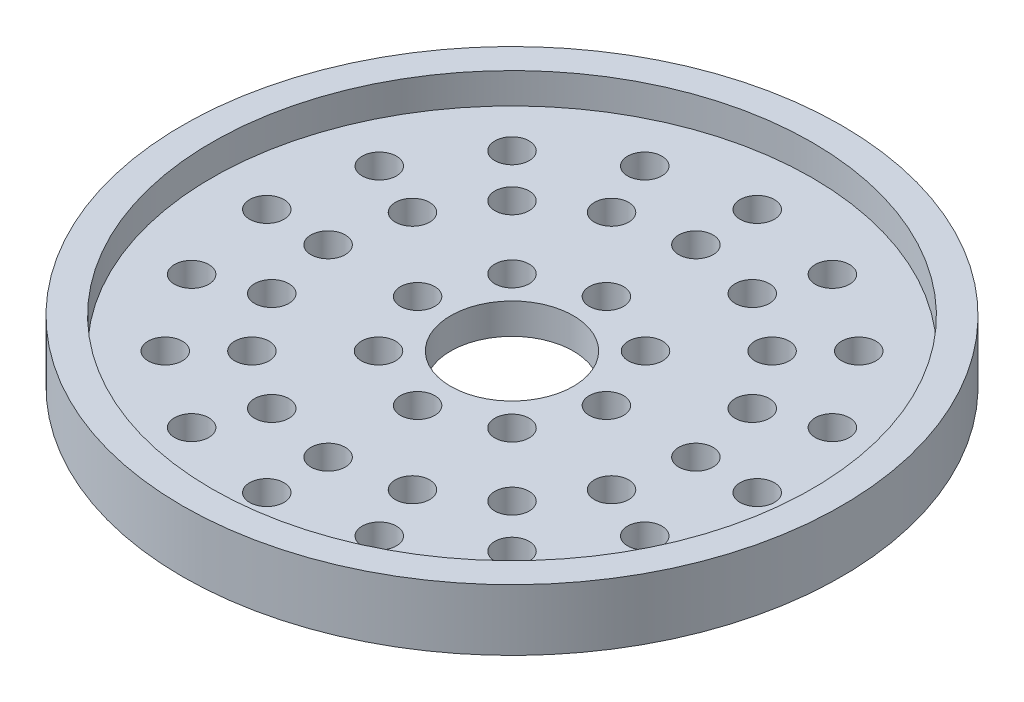
SolidWorks part; units mm, degrees
material "6061-T6 (SS)"
ref_plane "Front Plane" through (0, 0, 0) normal (0, 0, 1) x (1, 0, 0)
ref_plane "Top Plane" through (0, 0, 0) normal (0, 1, 0) x (1, 0, 0)
ref_plane "Right Plane" through (0, 0, 0) normal (1, 0, 0) x (0, 0, -1)
sketch "Sketch1" plane through (0, 0, 0) normal (0, 1, 0) x (1, 0, 0)
  circle A0 centre (0, 0) radius 34.1376
  dimension "D1" = 68.2752
extrude "Boss-Extrude1" add sketch "Sketch1" along normal blind 6.35
sketch "Sketch2" plane through (0, 6.35, 0) normal (0, 1, 0) x (1, 0, 0)
  circle A0 centre (0, 0) radius 31.0896
  circle A1 centre (0, 0) radius 34.1376 construction
  dimension "D1" = 3.048
extrude "Cut-Extrude3" cut sketch "Sketch2" against normal blind 3.175
sketch "Sketch3" plane through (0, 3.175, 0) normal (0, 1, 0) x (1, 0, 0)
  line L0 (0, 0) -> (0, 25.4) construction
  line L1 (0, 0) -> (0, -25.4) construction
  line L2 (0, 0) -> (25.4, 0) construction
  line L3 (0, 0) -> (-25.4, 0) construction
  line L4 (0, 0) -> (17.9605, 17.9605) construction
  line L5 (0, 0) -> (-17.9605, 17.9605) construction
  line L6 (0, 0) -> (-17.9605, -17.9605) construction
  line L7 (0, 0) -> (17.9605, -17.9605) construction
  circle A0 centre (0, 0) radius 6.35
  circle A1 centre (25.4, 0) radius 1.778
  circle A2 centre (17.9605, 17.9605) radius 1.778
  circle A3 centre (0, 25.4) radius 1.778
  circle A4 centre (-17.9605, 17.9605) radius 1.778
  circle A5 centre (-25.4, 0) radius 1.778
  circle A6 centre (-17.9605, -17.9605) radius 1.778
  circle A7 centre (0, -25.4) radius 1.778
  circle A8 centre (17.9605, -17.9605) radius 1.778
  dimension "D1" = 12.7
  dimension "D2" = 3.556
  dimension "D3" = 25.4
  dimension "D4" = 35.921
  dimension "D5" = 35.921
extrude "Cut-Extrude4" cut sketch "Sketch3" against normal blind 3.175 contours A0
sketch "Sketch7" plane through (0, 3.175, 0) normal (0, 1, 0) x (1, 0, 0)
  line L0 (0, 0) -> (0, 25.4) construction
  line L1 (0, 0) -> (0, 19.05) construction
  line L2 (0, 0) -> (0, 9.779) construction
  line L3 (-3.5469, 0) -> (3.6351, 0) construction
  line L4 (0, 0) -> (25.4, 0) construction
  line L5 (0, 0) -> (19.05, 0) construction
  line L6 (0, 0) -> (9.779, 0) construction
  line L7 (0, 0) -> (17.9605, 17.9605) construction
  line L8 (0, 0) -> (13.4704, 13.4704) construction
  line L9 (0, 0) -> (6.9148, 6.9148) construction
  line L10 (0, 0) -> (-3.5469, 3.5469) construction
  line L11 (0, 0) -> (3.0784, -3.0784) construction
  line L12 (0, 0) -> (6.9148, -6.9148) construction
  line L13 (0, 0) -> (13.4704, -13.4704) construction
  line L14 (0, 0) -> (17.9605, -17.9605) construction
  line L15 (0, 0) -> (9.7202, 23.4665) construction
  line L16 (0, 0) -> (7.2901, 17.5999) construction
  line L17 (0, 0) -> (3.7423, 9.0346) construction
  line L18 (-3.2361, 1.3404) -> (0, 0) construction
  line L19 (0, 0) -> (2.9979, -1.2418) construction
  line L20 (-1.5748, 3.8018) -> (0, 0) construction
  line L21 (0, 0) -> (1.5748, -3.8018) construction
  line L22 (0, 0) -> (-25.4, 0) construction
  circle A0 centre (0, 0) radius 25.4 construction
  circle A1 centre (0, 0) radius 19.05 construction
  circle A2 centre (0, 0) radius 9.779 construction
  circle A3 centre (0, 25.4) radius 1.778
  circle A4 centre (-9.7202, 23.4665) radius 1.778
  circle A5 centre (-17.9605, 17.9605) radius 1.778
  circle A6 centre (-23.4665, 9.7202) radius 1.778
  circle A7 centre (-25.4, 0) radius 1.778
  circle A8 centre (-23.4665, -9.7202) radius 1.778
  circle A9 centre (-17.9605, -17.9605) radius 1.778
  circle A10 centre (-9.7202, -23.4665) radius 1.778
  circle A11 centre (0, -25.4) radius 1.778
  circle A12 centre (9.7202, -23.4665) radius 1.778
  circle A13 centre (17.9605, -17.9605) radius 1.778
  circle A14 centre (23.4665, -9.7202) radius 1.778
  circle A15 centre (25.4, 0) radius 1.778
  circle A16 centre (23.4665, 9.7202) radius 1.778
  circle A17 centre (17.9605, 17.9605) radius 1.778
  circle A18 centre (9.7202, 23.4665) radius 1.778
  circle A19 centre (7.2901, 17.5999) radius 1.778
  circle A20 centre (13.4704, 13.4704) radius 1.778
  circle A21 centre (17.5999, 7.2901) radius 1.778
  circle A22 centre (19.05, 0) radius 1.778
  circle A23 centre (17.5999, -7.2901) radius 1.778
  circle A24 centre (13.4704, -13.4704) radius 1.778
  circle A25 centre (7.2901, -17.5999) radius 1.778
  circle A26 centre (0, -19.05) radius 1.778
  circle A27 centre (-7.2901, -17.5999) radius 1.778
  circle A28 centre (-13.4704, -13.4704) radius 1.778
  circle A29 centre (-17.5999, -7.2901) radius 1.778
  circle A30 centre (-19.05, 0) radius 1.778
  circle A31 centre (-17.5999, 7.2901) radius 1.778
  circle A32 centre (-13.4704, 13.4704) radius 1.778
  circle A33 centre (-7.2901, 17.5999) radius 1.778
  circle A34 centre (0, 19.05) radius 1.778
  circle A36 centre (0, 9.779) radius 1.778
  circle A38 centre (-6.9148, 6.9148) radius 1.778
  circle A40 centre (-9.779, 0) radius 1.778
  circle A42 centre (-6.9148, -6.9148) radius 1.778
  circle A44 centre (0, -9.779) radius 1.778
  circle A46 centre (6.9148, -6.9148) radius 1.778
  circle A48 centre (9.779, 0) radius 1.778
  circle A50 centre (6.9148, 6.9148) radius 1.778
  point P9 (0, -9.779)
  point P10 (0, -25.4)
  point P11 (0, -19.05)
  point P15 (-25.4, 0)
  point P19 (-19.05, 0)
  point P20 (-9.779, 0)
  point P25 (-3.7423, -9.0346)
  point P27 (-7.2901, -17.5999)
  point P28 (-9.7202, -23.4665)
  point P29 (23.4665, 9.7202)
  point P30 (17.5999, 7.2901)
  point P31 (9.0346, 3.7423)
  point P32 (23.4665, -9.7202)
  point P33 (17.5999, -7.2901)
  point P34 (9.0346, -3.7423)
  point P35 (9.7202, -23.4665)
  point P36 (7.2901, -17.5999)
  point P37 (3.7423, -9.0346)
  point P38 (-3.7423, 9.0346)
  point P39 (-6.9148, -6.9148)
  point P45 (-13.4704, -13.4704)
  point P46 (-17.9605, -17.9605)
  point P47 (-17.9605, 17.9605)
  point P51 (-13.4704, 13.4704)
  point P52 (-6.9148, 6.9148)
  point P53 (-7.2901, 17.5999)
  point P54 (-9.7202, 23.4665)
  point P56 (-9.0346, -3.7423)
  point P58 (-17.5999, -7.2901)
  point P59 (-23.4665, -9.7202)
  point P60 (-9.0346, 3.7423)
  point P62 (-17.5999, 7.2901)
  point P63 (-23.4665, 9.7202)
  dimension "D3" = 9.779
  dimension "D1" = 25.4
  dimension "D4" = 22.5
  dimension "D10" = 3.556
  dimension "D2" = 19.05
  dimension "D5" = 45
  dimension "D6" = 90
  dimension "D7" = 45
  dimension "D8" = 90
  dimension "D9" = 45
extrude "Cut-Extrude5" cut sketch "Sketch7" against normal up to surface (3.175 mm away) up to face at (0, 0, 6.35)
